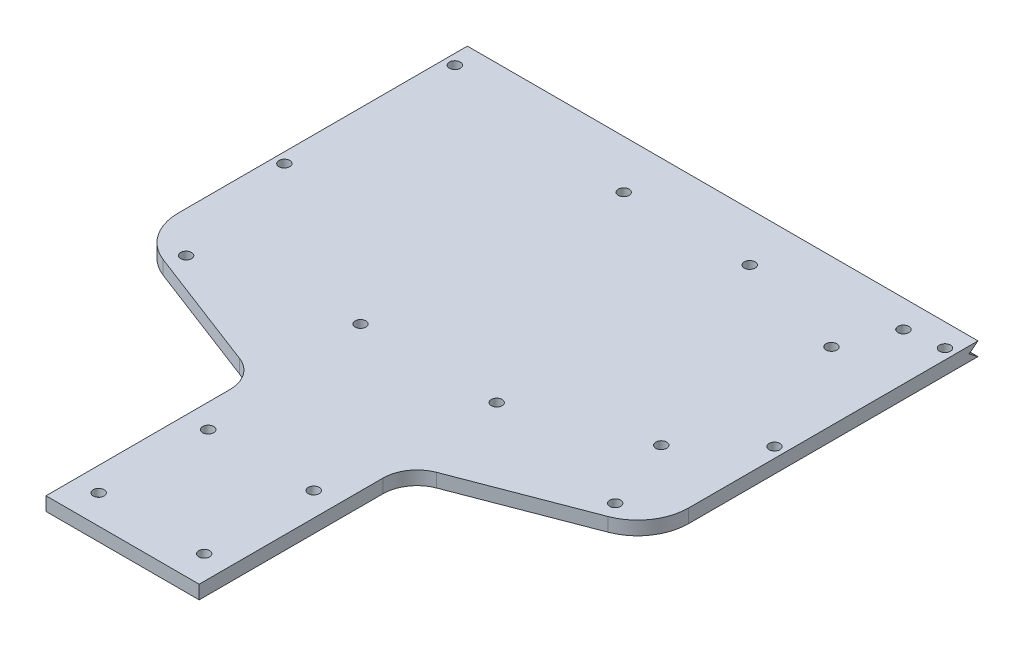
SolidWorks part; units mm, degrees
ref_plane "Plan de face" through (0, 0, 0) normal (0, 0, 1) x (1, 0, 0)
ref_plane "Plan de dessus" through (0, 0, 0) normal (0, 1, 0) x (1, 0, 0)
ref_plane "Plan de droite" through (0, 0, 0) normal (1, 0, 0) x (0, 0, -1)
sketch "Esquisse1" plane through (0, 0, 0) normal (0, -1, 0) x (1, 0, 0)
  line L0 (22.5, 171.3) -> (22.5, 117.3)
  line L1 (28.9241, 107.9612) -> (65.3638, 94.0082)
  line L2 (75, 80) -> (75, -80)
  line L3 (67.3157, -93.095) -> (27.6229, -115.27)
  line L4 (22.5, -124) -> (22.5, -178)
  line L14 (22.5, 171.3) -> (-22.5, 171.3)
  line L18 (0, 171.3) -> (0, -178) construction
  line L20 (-22.5, -178) -> (22.5, -178)
  line L22 (-22.5, -124) -> (-22.5, -178)
  line L23 (-67.3157, -93.095) -> (-27.6229, -115.27)
  line L25 (-75, 80) -> (-75, -80)
  line L26 (-28.9241, 107.9612) -> (-65.3638, 94.0082)
  line L27 (-22.5, 171.3) -> (-22.5, 117.3)
  arc A0 (28.9241, 107.9612) -> (22.5, 117.3) centre (32.5, 117.3) cw
  arc A1 (65.3638, 94.0082) -> (75, 80) centre (60, 80) cw
  arc A2 (75, -80) -> (67.3157, -93.095) centre (60, -80) cw
  arc A3 (22.5, -124) -> (27.6229, -115.27) centre (32.5, -124) cw
  arc A12 (-22.5, -124) -> (-27.6229, -115.27) centre (-32.5, -124) ccw
  arc A13 (-75, -80) -> (-67.3157, -93.095) centre (-60, -80) ccw
  arc A14 (-65.3638, 94.0082) -> (-75, 80) centre (-60, 80) ccw
  arc A15 (-28.9241, 107.9612) -> (-22.5, 117.3) centre (-32.5, 117.3) ccw
  point P18 (0, -178)
  point P19 (0, 171.3)
  point P36 (-75, 0)
  dimension "D7" = 15
  dimension "D8" = 10
  dimension "D1" = 150
  dimension "D2" = 45
  dimension "D3" = 349.3
  dimension "D4" = 54
  dimension "D5" = 54
  dimension "D6" = 44
  dimension "D9" = 178
  dimension "D10" = 75
extrude "Boss.-Extru.1" add sketch "Esquisse1" along normal blind 4
hole_wizard "Fraisage pour vis à tête fraisée M31" positions "Esquisse3" profile "Esquisse2" countersink size "M3" standard "Ansi Metric" end condition up to next
sketch "Esquisse3" plane through (0, -4, 0) normal (0, -1, 0) x (-1, 0, 0)
  line L0 (-75, 80) -> (-75, -80) construction
  line L1 (22.5, 124) -> (22.5, 178) construction
  line L2 (22.5, 178) -> (-22.5, 178) construction
  line L3 (-22.5, 178) -> (-22.5, 124) construction
  line L4 (-75, 80) -> (-75, -80) construction
  point P0 (14.85, -9.22)
  point P3 (-22.15, -9.22)
  point P6 (-61.15, -3.06)
  point P9 (-61.15, 26.94)
  point P12 (-22.15, 22.78)
  point P15 (14.85, 22.78)
  point P18 (15.5, 137)
  point P21 (-15.5, 137)
  point P24 (15.5, 169)
  point P27 (-15.5, 169)
  point P30 (63.0257, -89.6123)
  point P32 (72, -51.7763)
  point P34 (72, 48.3763)
  point P36 (65.8526, 88.476)
  point P38 (26.643, 110.381)
  point P40 (-26.643, 110.381)
  point P42 (-65.8526, 88.476)
  point P44 (-72, 48.3763)
  point P46 (-63.0257, -89.6123)
  point P48 (-72, -51.7763)
  point P49 (20, -81.3983)
  point P51 (-20, -81.3983)
  point P59 (-72, -1.7)
  point P61 (72, -1.7)
  point P67 (-55, -68.06)
  point P71 (-55, -18.06)
  dimension "D1" = 13.85
  dimension "D2" = 15
  dimension "D3" = 30
  dimension "D4" = 32
  dimension "D5" = 37
  dimension "D6" = 39
  dimension "D7" = 6.16
  dimension "D8" = 7
  dimension "D9" = 32
  dimension "D10" = 9
  dimension "D11" = 7
  dimension "D12" = 22.78
  dimension "D13" = 50
  dimension "D14" = 20
sketch "Esquisse2" plane through (-14.85, -4, 9.22) normal (1, 0, 0) x (0, 0, -1)
  line L0 (0, 0) -> (0, 4)
  line L1 (0, 4) -> (1.6, 4)
  line L2 (1.6, 4) -> (1.6, 1.7)
  line L3 (1.6, 1.7) -> (2.9, 0.4)
  line L4 (2.9, 0.4) -> (2.9, 0)
  line L6 (2.9, 0) -> (0, 0)
  line L7 (-1.6, 1.7) -> (-2.9, 0.4) construction
  line L11 (0, -6.35) -> (0, 107.95) construction
  dimension "Diamètre du perçage jusqu'au prochain" = 3.2
  dimension "Profondeur du perçage jusqu'au prochain" = 4
  dimension "Diamètre du fraisage" = 5.8
  dimension "Angle du fraisage" = 90
  dimension "Dégagement de la tête" = 0.4
ref_plane "Plan1" through (15.5, 0, 0) normal (1, 0, 0) x (0, 0, -1)
sketch "Esquisse4" plane through (15.5, 0, 0) normal (1, 0, 0) x (0, 0, -1)
  line L0 (-130.4423, 1.9719) -> (-128.8511, 1.8047)
  line L1 (-133.8804, -2.9959) -> (-128.1122, -3.6022) construction
  line L2 (-128.8511, 1.8047) -> (-129.2692, -2.1734)
  line L3 (-129.2692, -2.1734) -> (-128.1122, -3.6022)
  line L4 (-128.1122, -3.6022) -> (-128.2177, -4.6063)
  line L5 (-133.9223, -3.3937) -> (-128.154, -4) construction
  line L6 (-130.4423, 1.9719) -> (-131.1019, -4.3031)
  line L7 (-131.1019, -4.3031) -> (-128.2177, -4.6063)
  line L8 (-171.3, -4) -> (-171.3, 0) construction
  line L10 (-131.1019, -4.3031) -> (-133.986, -4) construction
  line L12 (-117.3, -4) -> (-171.3, -4) construction
  line L13 (-133.986, -4) -> (-133.8804, -2.9959) construction
  line L14 (-133.8804, -2.9959) -> (-130.6932, -0.4149) construction
  line L15 (-129.2692, -2.1734) -> (-130.6932, -0.4149) construction
  point P19 (-131.07, -4)
  dimension "D1" = 90
  dimension "D2" = 5.8
  dimension "D3" = 0.4
  dimension "D4" = 1.6
  dimension "D5" = 4
  dimension "D6" = 84
  dimension "D7" = 40.23
revolve "Enlèvement de matière-Révolution1" cut sketch "Esquisse4" angle 360 about L6
sketch "Esquisse6" plane through (15.5, 0, 0) normal (1, 0, 0) x (0, 0, -1)
  line L0 (-162.8258, 0) -> (-163.2463, -4) construction
  line L1 (-117.3, -4) -> (-171.3, -4) construction
  line L2 (-117.3, 0) -> (-171.3, 0) construction
  line L5 (-130.6496, 0) -> (-131.07, -4) construction
  dimension "D1" = 84
  dimension "D2" = 32
sketch "Esquisse5" plane through (15.5, 0, 0) normal (1, 0, 0) x (0, 0, -1)
  line L0 (-162.7555, 0.6689) -> (-161.1643, 0.5017)
  line L1 (-161.1643, 0.5017) -> (-161.4453, -2.1714)
  line L2 (-161.4453, -2.1714) -> (-160.2849, -3.6026)
  line L3 (-160.2849, -3.6026) -> (-160.3302, -4)
  line L4 (-160.3302, -4) -> (-160.3993, -4.6063)
  line L5 (-160.3993, -4.6063) -> (-163.2782, -4.3037)
  line L6 (-163.2782, -4.3037) -> (-166.1677, -4) construction
  line L7 (-166.1677, -4) -> (-166.0986, -3.3937) construction
  line L8 (-166.0533, -2.9963) -> (-162.8694, -0.4148) construction
  line L9 (-162.7555, 0.6689) -> (-163.2782, -4.3037)
  line L10 (-166.0986, -3.3937) -> (-166.0533, -2.9963) construction
  line L11 (-160.3302, -4) -> (-166.0986, -3.3937) construction
  line L12 (-162.8258, 0) -> (-163.2463, -4) construction
  line L13 (-171.3, -4) -> (-117.3, -4) construction
  line L14 (-157.2606, -6.1647) -> (-155.7772, 6.8554) construction
  line L16 (-117.3, -4) -> (-171.3, -4) construction
  line L17 (-161.4453, -2.1714) -> (-162.8694, -0.4148) construction
  point P11 (-163.2144, -3.6969)
  point P20 (-163.2463, -4)
  dimension "D1" = 5.8
  dimension "D2" = 0.4
  dimension "D3" = 90
  dimension "D4" = 1.6
  dimension "D6" = 5
revolve "Enlèvement de matière-Révolution2" cut sketch "Esquisse5" angle 360 about L9
mirror "Symétrie1" about plane through (0, 0, 0) normal (1, 0, 0) of "Enlèvement de matière-Révolution2", "Enlèvement de matière-Révolution1"
sketch "Esquisse7" plane through (0, 0, 0) normal (1, 0, 0) x (0, 0, -1)
  line L1 (5, 0) -> (178, 0)
  line L2 (5, 0) -> (5, -4)
  line L3 (5, -4) -> (178, -4)
  line L4 (178, 0) -> (178, -4)
  point P5 (178, -4)
  point P6 (6.8509, -4)
  dimension "D1" = 5
extrude "Enlèv. mat.-Extru.1" cut sketch "Esquisse7" against normal up to next and the other way up to next
sketch "Esquisse8" plane through (75, 0, 0) normal (1, 0, 0) x (0, 0, -1)
  line L0 (5, 0) -> (2.3935, -2)
  line L1 (2.3935, -2) -> (5, -4)
  line L2 (5, -4) -> (5, 0)
  line L3 (0, 0) -> (0, -4) construction
  line L4 (5, -4) -> (-80, -4) construction
  line L5 (0, -2) -> (5, -2) construction
  point P12 (1.9868, -2)
  dimension "D1" = 75
extrude "Enlèv. mat.-Extru.2" cut sketch "Esquisse8" against normal up to next
